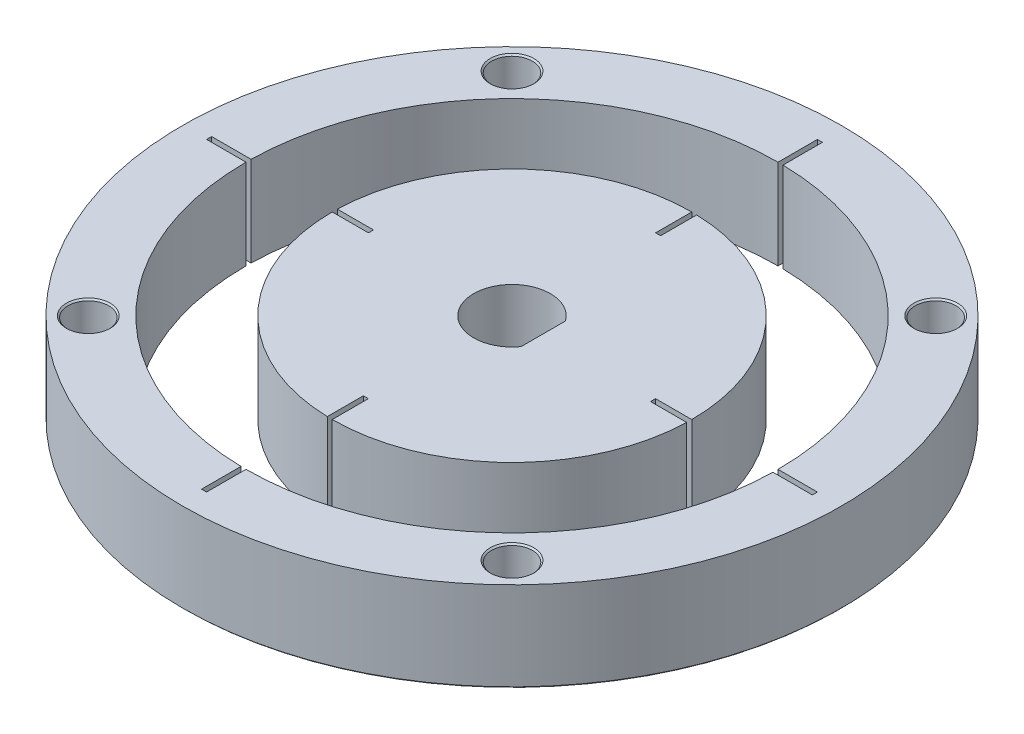
SolidWorks part; units mm, degrees
ref_plane "Front Plane" through (0, 0, 0) normal (0, 0, 1) x (1, 0, 0)
ref_plane "Top Plane" through (0, 0, 0) normal (0, 1, 0) x (1, 0, 0)
ref_plane "Right Plane" through (0, 0, 0) normal (1, 0, 0) x (0, 0, -1)
sketch "Sketch2" plane through (0, 0, 0) normal (0, 1, 0) x (1, 0, 0)
  line L0 (0, -15) -> (0, -11.9832)
  line L1 (0, -11.9832) -> (-0.175, -11.9832)
  line L2 (-15, 0) -> (-11.9832, 0)
  line L3 (0, -11.9832) -> (-0.42, -11.9832)
  line L4 (-0.42, -11.9832) -> (-0.42, -14.9941)
  line L5 (-11.9832, 0.42) -> (-14.9941, 0.42)
  line L6 (-11.9832, 0) -> (-11.9832, 0.42)
  line L7 (0, 15) -> (0, 11.9832)
  line L8 (0.42, 11.9832) -> (0.42, 14.9941)
  line L9 (0, 11.9832) -> (0.42, 11.9832)
  line L10 (15, 0) -> (11.9832, 0)
  line L11 (11.9832, -0.42) -> (14.9941, -0.42)
  line L12 (11.9832, 0) -> (11.9832, -0.42)
  arc A0 (0, -15) -> (14.9941, -0.42) centre (0, 0) ccw
  arc A1 (-0.42, -14.9941) -> (0, -15) centre (0, 0) ccw construction
  arc A2 (-15, 0) -> (-0.42, -14.9941) centre (0, 0) ccw
  arc A3 (-14.9941, 0.42) -> (-15, 0) centre (0, 0) ccw construction
  arc A4 (0, 15) -> (-14.9941, 0.42) centre (0, 0) ccw
  arc A5 (0.42, 14.9941) -> (0, 15) centre (0, 0) ccw construction
  arc A6 (15, 0) -> (0.42, 14.9941) centre (0, 0) ccw
  arc A7 (14.9941, -0.42) -> (15, 0) centre (0, 0) ccw construction
  circle A8 centre (0, 0) radius 22.1975
  circle A9 centre (0, 0) radius 27.5
  point P22 (0, 0)
  dimension "D1" = 30
  dimension "D3" = 55
  dimension "D2" = 4
  dimension "D4" = 0.42
extrude "Boss-Extrude3" add sketch "Sketch2" along normal blind 7.5 contours L0 A0 L11 L12 L10 A6 L8 L9 L7 A4 L5 L6 L2 A2 L4 L3 | A8 | A9
sketch "Sketch4" plane through (0, 7.5, 0) normal (0, 1, 0) x (1, 0, 0)
  circle A0 centre (0, 0) radius 27.5
  dimension "D1" = 55
sketch "Sketch5" plane through (0, 0, 0) normal (0, -1, 0) x (1, 0, 0)
  line L0 (0, -11.9832) -> (0, -25.4832)
  line L1 (0.42, -11.9832) -> (0.42, -25.4832)
  line L2 (0, -25.4832) -> (0.42, -25.4832)
  line L3 (-25.4832, 0) -> (-25.4832, -0.42)
  line L4 (-11.9832, -0.42) -> (-25.4832, -0.42)
  line L5 (-11.9832, 0) -> (-25.4832, 0)
  line L6 (0, 25.4832) -> (-0.42, 25.4832)
  line L7 (-0.42, 11.9832) -> (-0.42, 25.4832)
  line L8 (0, 11.9832) -> (0, 25.4832)
  line L9 (25.4832, 0) -> (25.4832, 0.42)
  line L10 (11.9832, 0.42) -> (25.4832, 0.42)
  line L11 (11.9832, 0) -> (25.4832, 0)
  line L12 (0, -11.9832) -> (0.42, -11.9832)
  line L13 (11.9832, 0.42) -> (11.9832, 0)
  line L14 (-11.9832, 0) -> (-11.9832, -0.42)
  line L15 (-0.42, 11.9832) -> (0, 11.9832)
  circle A0 centre (-17.6777, 17.6777) radius 1.7
  circle A1 centre (17.6777, 17.6777) radius 1.7
  circle A2 centre (17.6777, -17.6777) radius 1.7
  circle A3 centre (-17.6777, -17.6777) radius 1.7
  point P22 (0, 0)
  point P28 (0, 0)
  point P36 (0, 0)
  dimension "D3" = 3.4
  dimension "D2" = 13.5
  dimension "D1" = 4
  dimension "D5" = 4
sketch "Sketch7" plane through (0, 0, 0) normal (0, -1, 0) x (1, 0, 0)
  line L0 (2.611, 1.85) -> (2.611, -1.85)
  arc A0 (2.611, 1.85) -> (2.611, -1.85) centre (0, 0) ccw
  arc A1 (2.611, -1.85) -> (2.611, 1.85) centre (0, 0) ccw construction
  dimension "D1" = 6.4
extrude "Cut-Extrude6" cut sketch "Sketch5" against normal through all contours L0 L2 L1 L12 | L5 L3 L4 L14 | A0 | L7 L6 L8 L15 | A1 | L11 L9 L10 L13 | A2 | A3
extrude "Cut-Extrude8" cut sketch "Sketch7" against normal blind 7.5 contours A0 L0
chamfer "Chamfer3" distance 0.125 angle 45 2 edges at (2.611, 0, 0) (-3.2, 0, 0)
chamfer "Chamfer4" distance 0.125 angle 45 9 edges at (0, 0, 27.5) (17.6777, 0, 15.9777) (17.6777, 0, -19.3777) (-17.6777, 0, -19.3777) (-17.6777, 0, 15.9777) (-17.6777, 7.5, 15.9777) (17.6777, 7.5, 15.9777) (17.6777, 7.5, -19.3777) (-17.6777, 7.5, -19.3777)
